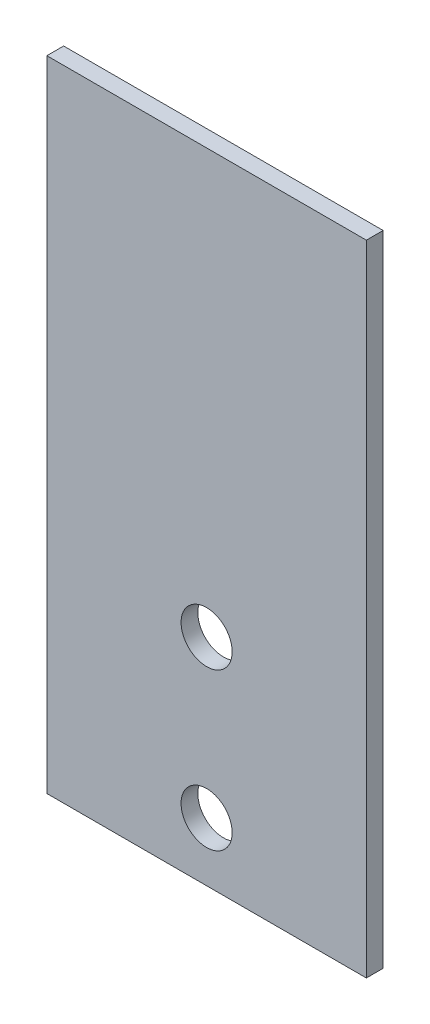
SolidWorks part; units mm, degrees
ref_plane "Front Plane" through (0, 0, 0) normal (0, 0, 1) x (1, 0, 0)
ref_plane "Top Plane" through (0, 0, 0) normal (0, 1, 0) x (1, 0, 0)
ref_plane "Right Plane" through (0, 0, 0) normal (1, 0, 0) x (0, 0, -1)
sketch "Sketch1" plane through (0, 0, 0) normal (0, 0, 1) x (1, 0, 0)
  line L0 (0, 19.1606) -> (0, 60.4474) construction
  line L1 (3.4656, 19.1606) -> (-3.4656, 19.1606) construction
  line L3 (-9.525, 20.492) -> (9.525, 20.492)
  line L4 (-9.525, 20.492) -> (-9.525, 58.592)
  line L5 (-9.525, 58.592) -> (9.525, 58.592)
  line L6 (9.525, 20.492) -> (9.525, 58.592)
  circle A0 centre (0, 33.332) radius 1.524
  circle A1 centre (0, 23.992) radius 1.524
  point P9 (0, 58.592)
  dimension "D4" = 3.048
  dimension "D1" = 3.5
  dimension "D2" = 19.05
  dimension "D3" = 38.1
extrude "Boss-Extrude1" add sketch "Sketch1" along normal blind 1
